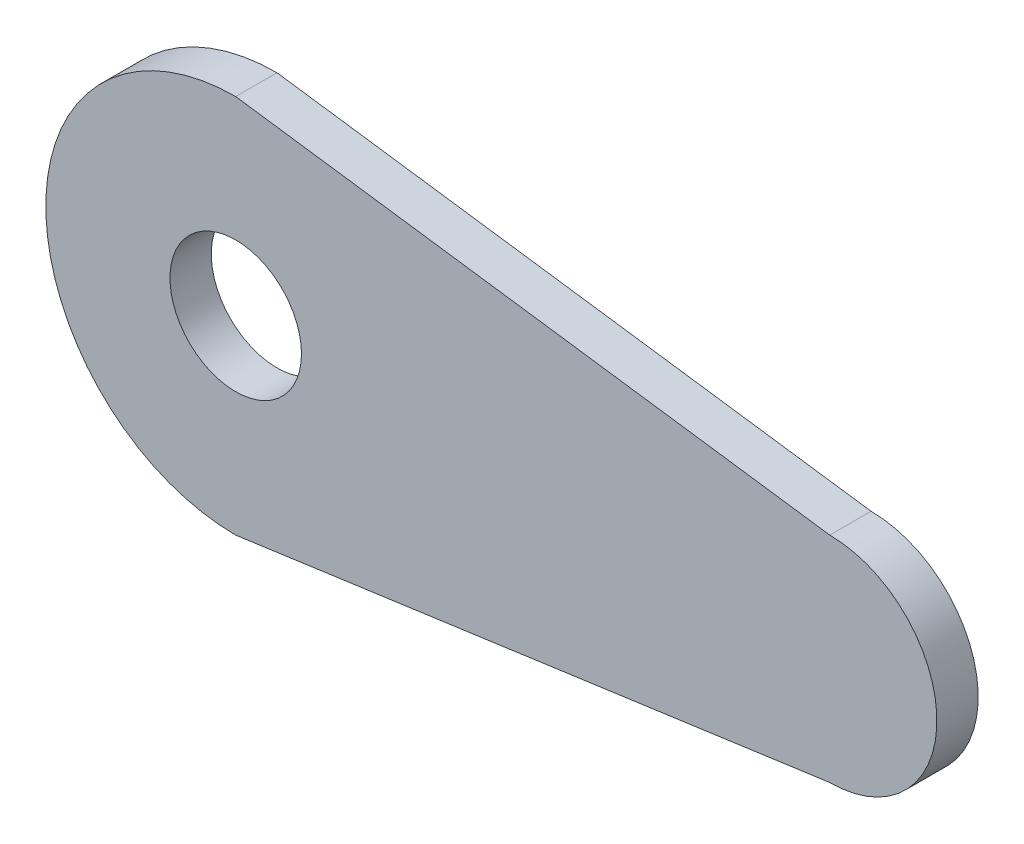
SolidWorks part; units mm, degrees
ref_plane "Front Plane" through (0, 0, 0) normal (0, 0, 1) x (1, 0, 0)
ref_plane "Top Plane" through (0, 0, 0) normal (0, 1, 0) x (1, 0, 0)
ref_plane "Right Plane" through (0, 0, 0) normal (1, 0, 0) x (0, 0, -1)
sketch "Sketch3" plane through (0, 0, 0) normal (0, 0, 1) x (1, 0, 0)
  line L0 (0, 0) -> (359.7386, 0)
  line L1 (0, 115) -> (359.7386, 64.8806)
  line L2 (359.7386, -64.8806) -> (0, -115)
  circle A0 centre (0, 0) radius 115
  circle A1 centre (359.7386, 0) radius 64.8806
  circle A2 centre (0, 0) radius 39.8164
extrude "Boss-Extrude2" add sketch "Sketch3" along normal blind 25
